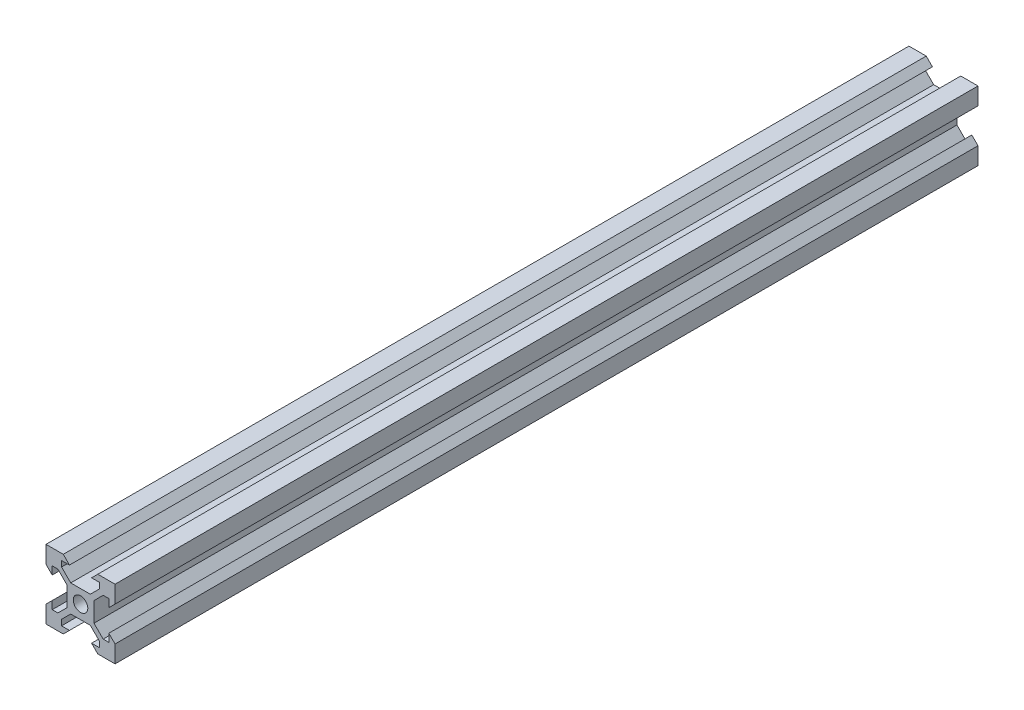
SolidWorks part; units mm, degrees
material "6063-T5"
ref_plane "Front Plane" through (0, 0, 0) normal (0, 0, 1) x (1, 0, 0)
ref_plane "Top Plane" through (0, 0, 0) normal (0, 1, 0) x (1, 0, 0)
ref_plane "Right Plane" through (0, 0, 0) normal (1, 0, 0) x (0, 0, -1)
sketch "Sketch1" plane through (0, 0, 0) normal (0, 0, 1) x (1, 0, 0)
  line L0 (-10, 10) -> (-5, 10)
  line L1 (10, -10) -> (-10, -10) construction
  line L2 (10, -10) -> (10, 10) construction
  line L3 (10, 10) -> (-10, 10) construction
  line L4 (-10, -10) -> (-10, 10) construction
  line L5 (10, -10) -> (-10, 10) construction
  line L6 (10, 10) -> (-10, -10) construction
  line L7 (-5, 10) -> (-3.2, 8.2)
  line L8 (-3.2, 8.2) -> (-5.4993, 8.2)
  line L9 (-5.4993, 8.2) -> (-5.4993, 6.56)
  line L10 (-2.84, 3.9007) -> (2.84, 3.9007)
  line L11 (0, 3.9007) -> (0, 2.1) construction
  line L12 (-5.4993, 6.56) -> (-2.84, 3.9007)
  line L13 (0, 0) -> (0, -13.2939) construction
  line L14 (0, 0) -> (-17.0802, 0) construction
  line L15 (-10, 10) -> (-10, 5)
  line L16 (-10, 5) -> (-8.2, 3.2)
  line L17 (-8.2, 3.2) -> (-8.2, 5.4993)
  line L18 (-8.2, 5.4993) -> (-6.56, 5.4993)
  line L19 (-6.56, 5.4993) -> (-3.9007, 2.84)
  line L20 (-3.9007, 2.84) -> (-3.9007, -2.84)
  line L21 (-3.2, -8.2) -> (-5.4993, -8.2)
  line L22 (-5.4993, -8.2) -> (-5.4993, -6.56)
  line L23 (-5, -10) -> (-3.2, -8.2)
  line L24 (-10, -10) -> (-5, -10)
  line L25 (-10, -10) -> (-10, -5)
  line L26 (-10, -5) -> (-8.2, -3.2)
  line L27 (-8.2, -3.2) -> (-8.2, -5.4993)
  line L28 (-8.2, -5.4993) -> (-6.56, -5.4993)
  line L29 (-6.56, -5.4993) -> (-3.9007, -2.84)
  line L30 (-5.4993, -6.56) -> (-2.84, -3.9007)
  line L31 (-2.84, -3.9007) -> (2.84, -3.9007)
  line L32 (5.4993, 6.56) -> (2.84, 3.9007)
  line L33 (3.2, 8.2) -> (5.4993, 8.2)
  line L34 (5.4993, 8.2) -> (5.4993, 6.56)
  line L35 (5, 10) -> (3.2, 8.2)
  line L36 (10, 10) -> (5, 10)
  line L37 (10, 10) -> (10, 5)
  line L38 (10, 5) -> (8.2, 3.2)
  line L39 (8.2, 3.2) -> (8.2, 5.4993)
  line L40 (8.2, 5.4993) -> (6.56, 5.4993)
  line L41 (6.56, 5.4993) -> (3.9007, 2.84)
  line L42 (3.9007, 2.84) -> (3.9007, -2.84)
  line L43 (6.56, -5.4993) -> (3.9007, -2.84)
  line L44 (8.2, -5.4993) -> (6.56, -5.4993)
  line L45 (8.2, -3.2) -> (8.2, -5.4993)
  line L46 (10, -5) -> (8.2, -3.2)
  line L47 (10, -10) -> (10, -5)
  line L48 (10, -10) -> (5, -10)
  line L49 (5, -10) -> (3.2, -8.2)
  line L50 (3.2, -8.2) -> (5.4993, -8.2)
  line L51 (5.4993, -8.2) -> (5.4993, -6.56)
  line L52 (5.4993, -6.56) -> (2.84, -3.9007)
  circle A0 centre (0, 0) radius 2.1
  arc A1 (0, -2.1) -> (0, 2.1) centre (0, 0) cw construction
  point P0 (0, 0)
  point P25 (-3.9007, 0)
  point P35 (0, 0)
  point P56 (0, -3.9007)
  dimension "D2" = 4.2
  dimension "D1" = 20
  dimension "D3" = 1.64
  dimension "D4" = 1.8
  dimension "D5" = 45
  dimension "D6" = 1.5
  dimension "D7" = 5.68
  dimension "D8" = 5
extrude "Boss-Extrude1" add sketch "Sketch1" along normal mid plane 250
